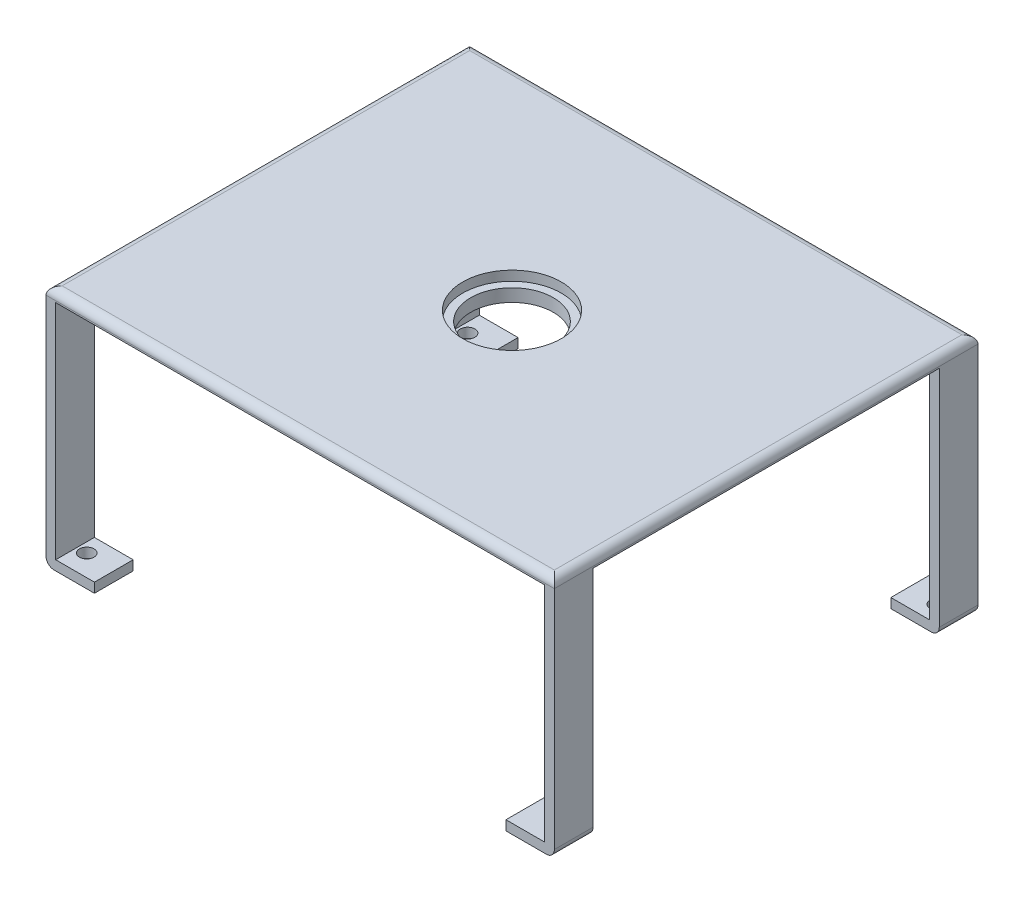
SolidWorks part; units mm, degrees
ref_plane "Plan de face" through (0, 0, 0) normal (0, 0, 1) x (1, 0, 0)
ref_plane "Plan de dessus" through (0, 0, 0) normal (0, 1, 0) x (1, 0, 0)
ref_plane "Plan de droite" through (0, 0, 0) normal (1, 0, 0) x (0, 0, -1)
sketch "Esquisse2" plane through (0, 0, 0) normal (0, 0, 1) x (1, 0, 0)
  line L0 (-64.77, 0) -> (-80.01, 0)
  line L1 (-80.01, 0) -> (-80.01, 76.2)
  line L2 (-80.01, 76.2) -> (80.01, 76.2)
  line L3 (80.01, 76.2) -> (80.01, 0)
  line L4 (80.01, 0) -> (64.77, 0)
  line L5 (64.77, 0) -> (64.77, 3.048)
  line L6 (64.77, 3.048) -> (76.962, 3.048)
  line L7 (76.962, 3.048) -> (76.962, 73.152)
  line L8 (76.962, 73.152) -> (-76.962, 73.152)
  line L9 (-76.962, 73.152) -> (-76.962, 3.048)
  line L10 (-76.962, 3.048) -> (-64.77, 3.048)
  line L11 (-64.77, 3.048) -> (-64.77, 0)
  point P12 (0, 76.2)
  dimension "D1" = 160.02
  dimension "D2" = 76.2
  dimension "D3" = 3.048
  dimension "D4" = 3.048
  dimension "D5" = 3.048
  dimension "D6" = 15.24
extrude "Boss.-Extru.1" add sketch "Esquisse2" along normal blind 133.35
sketch "Esquisse3" plane through (-80.01, 0, 0) normal (-1, 0, 0) x (0, 0, 1)
  line L0 (133.35, 0) -> (0, 0) construction
  line L1 (12.192, 0) -> (121.158, 0)
  line L2 (12.192, 0) -> (12.192, 73.152)
  line L3 (12.192, 73.152) -> (121.158, 73.152)
  line L4 (121.158, 0) -> (121.158, 73.152)
  line L5 (133.35, 76.2) -> (0, 76.2) construction
  line L6 (0, 76.2) -> (0, 0) construction
  line L7 (133.35, 76.2) -> (133.35, 0) construction
  dimension "D1" = 3.048
  dimension "D2" = 12.192
  dimension "D3" = 12.192
extrude "Enlèv. mat.-Extru.1" cut sketch "Esquisse3" against normal through all
sketch "Esquisse4" plane through (0, 3.048, 0) normal (0, 1, 0) x (1, 0, 0)
  line L0 (80.01, -133.35) -> (80.01, 0) construction
  line L2 (80.01, 0) -> (-80.01, 0) construction
  circle A0 centre (73.914, -6.731) radius 2.286
  dimension "D1" = 4.572
  dimension "D2" = 6.096
  dimension "D3" = 6.731
extrude "Enlèv. mat.-Extru.2" cut sketch "Esquisse4" against normal through all
fillet "Congé1" radius 2.54 4 edges at (-80.01, 0, 127.254) (-80.01, 0, 6.096) (80.01, 0, 127.254) (80.01, 0, 6.096)
fillet "Congé2" radius 2.54 4 edges at (80.01, 76.2, 66.675) (0, 76.2, 133.35) (-80.01, 76.2, 66.675) (0, 76.2, 0)
sketch "Esquisse5" plane through (0, 3.048, 0) normal (0, 1, 0) x (1, 0, 0)
  line L0 (80.01, 0) -> (80.01, -133.35) construction
  circle A0 centre (73.914, -126.619) radius 2.286
  circle A1 centre (73.914, -6.731) radius 2.286 construction
  dimension "D1" = 4.572
  dimension "D2" = 6.096
  dimension "D3" = 119.888
extrude "Enlèv. mat.-Extru.3" cut sketch "Esquisse5" against normal through all
sketch "Esquisse6" plane through (0, 76.2, 0) normal (0, 1, 0) x (1, 0, 0)
  line L0 (-80.01, 0) -> (80.01, 0) construction
  line L1 (-80.01, -133.35) -> (-80.01, 0) construction
  circle A0 centre (0, -66.675) radius 15.5
  dimension "D1" = 31
  dimension "D2" = 66.675
  dimension "D3" = 80.01
extrude "Enlèv. mat.-Extru.4" cut sketch "Esquisse6" against normal through all
sketch "Esquisse7" plane through (0, 3.048, 0) normal (0, 1, 0) x (1, 0, 0)
  line L2 (-80.01, -133.35) -> (-80.01, 0) construction
  line L3 (80.01, -133.35) -> (-80.01, -133.35) construction
  circle A0 centre (-73.406, -126.746) radius 2.159
  dimension "D1" = 4.318
  dimension "D2" = 6.604
  dimension "D3" = 6.604
sketch "Esquisse8" plane through (0, 3.048, 0) normal (0, 1, 0) x (1, 0, 0)
  line L0 (-80.01, 0) -> (80.01, 0) construction
  line L1 (-80.01, -133.35) -> (-80.01, 0) construction
  circle A0 centre (-73.406, -6.604) radius 2.159
  dimension "D1" = 4.318
  dimension "D2" = 6.604
  dimension "D3" = 6.604
mirror "Symétrie1" about plane through (0, 0, 0) normal (1, 0, 0) of "Enlèv. mat.-Extru.3"
mirror "Symétrie2" about plane through (0, 0, 0) normal (1, 0, 0) of "Enlèv. mat.-Extru.2"
sketch "Sketch1" plane through (0, 73.152, 0) normal (0, -1, 0) x (1, 0, 0)
  circle A0 centre (0, 66.675) radius 17.5
  circle A1 centre (0, 66.675) radius 15.5 construction
  dimension "D1" = 35
extrude "Boss-Extrude1" add sketch "Sketch1" along normal blind 4
sketch "Sketch2" plane through (0, 73.152, 0) normal (0, 1, 0) x (1, 0, 0)
  circle A0 centre (0, -66.675) radius 13
  circle A1 centre (0, -66.675) radius 15.5 construction
  dimension "D1" = 26
extrude "Cut-Extrude1" cut sketch "Sketch2" against normal through all
